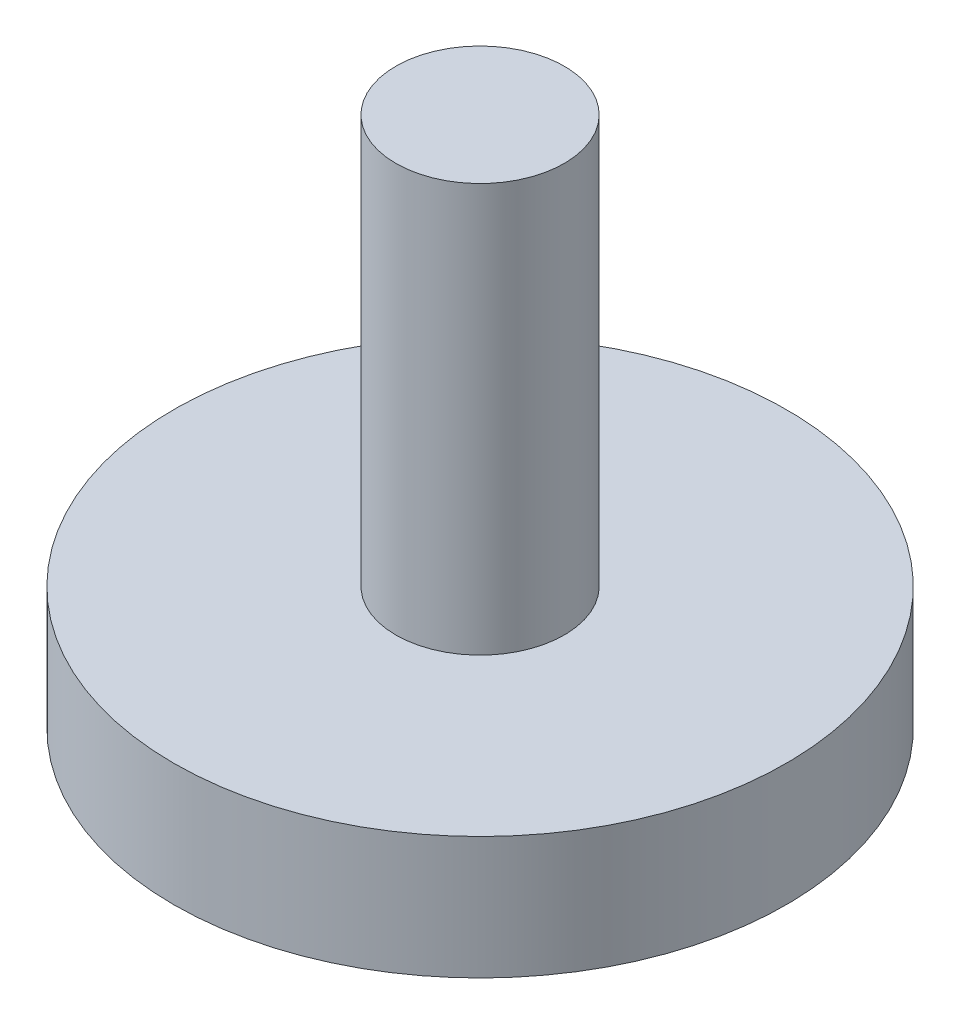
SolidWorks part; units mm, degrees
ref_plane "Front" through (0, 0, 0) normal (0, 0, 1) x (1, 0, 0)
ref_plane "Top" through (0, 0, 0) normal (0, 1, 0) x (1, 0, 0)
ref_plane "Right" through (0, 0, 0) normal (1, 0, 0) x (0, 0, -1)
sketch "스케치1" plane through (0, 0, 0) normal (0, 1, 0) x (1, 0, 0)
  circle A0 centre (0, 0) radius 7.5
  dimension "D1" = 15
extrude "보스-돌출1" add sketch "스케치1" along normal blind 3
sketch "스케치2" plane through (0, 3, 0) normal (0, 1, 0) x (1, 0, 0)
  circle A0 centre (0, 0) radius 2.0625
  dimension "D1" = 4.125
extrude "보스-돌출2" add sketch "스케치2" along normal blind 10
